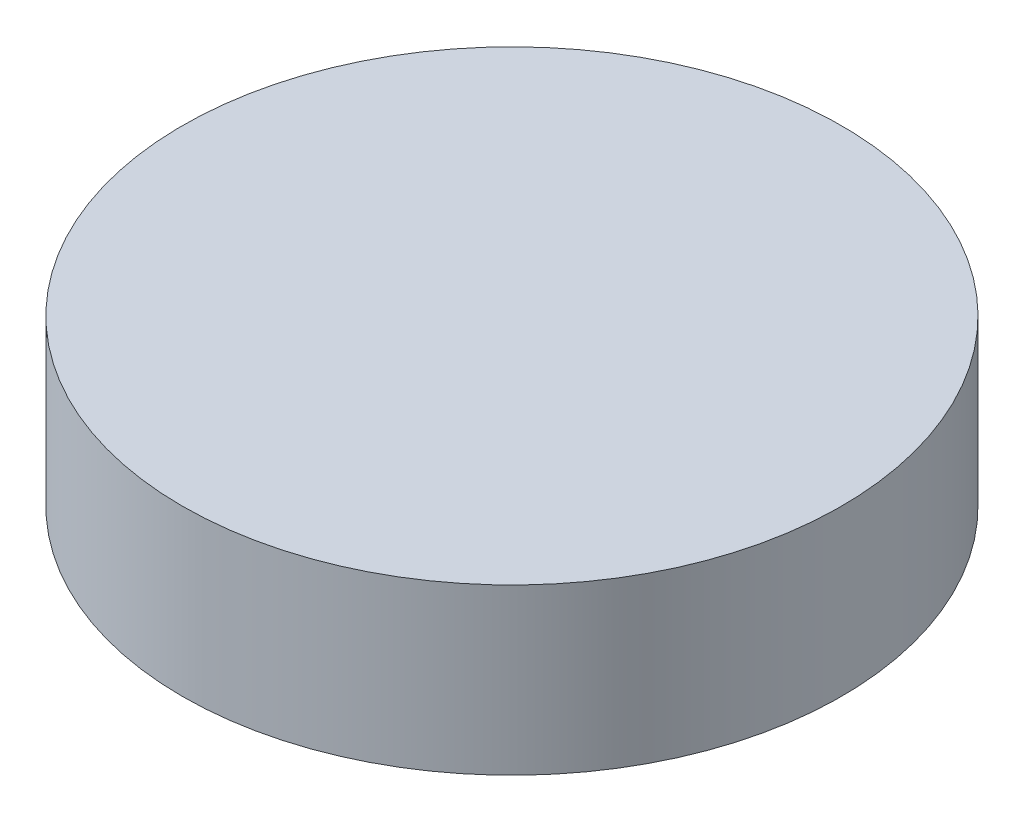
SolidWorks part; units mm, degrees
material "Vidrio"
ref_plane "Alzado" through (0, 0, 0) normal (0, 0, 1) x (1, 0, 0)
ref_plane "Planta" through (0, 0, 0) normal (0, 1, 0) x (1, 0, 0)
ref_plane "Vista lateral" through (0, 0, 0) normal (1, 0, 0) x (0, 0, -1)
sketch "Croquis1" plane through (0, 0, 0) normal (0, 1, 0) x (1, 0, 0)
  circle A0 centre (0, 0) radius 4
  dimension "D1" = 8
extrude "Saliente-Extruir1" add sketch "Croquis1" along normal blind 2
